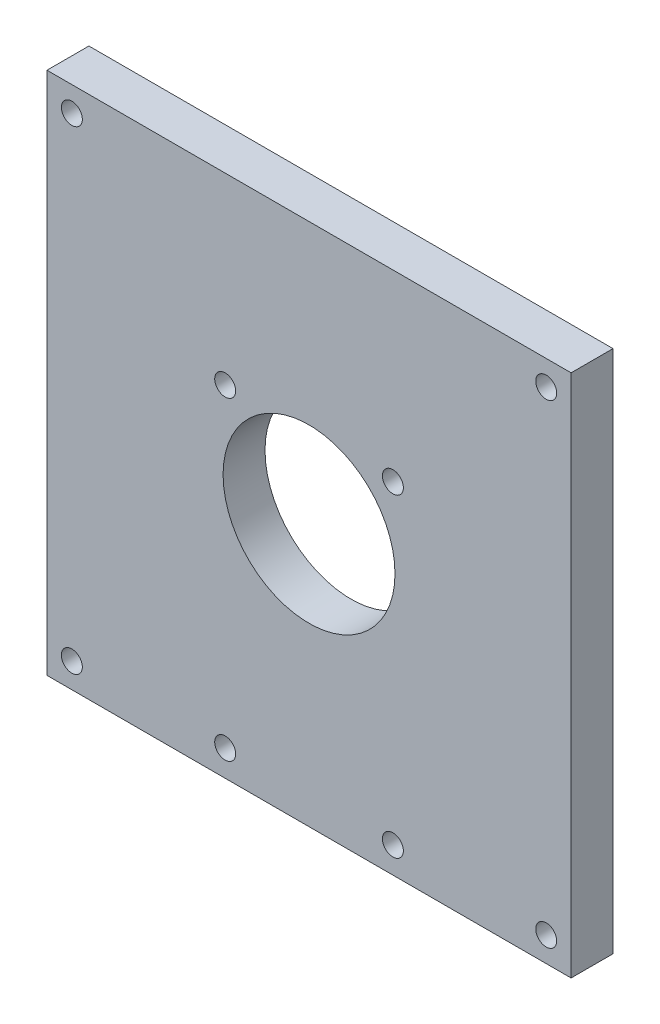
SolidWorks part; units mm, degrees
ref_plane "Front Plane" through (0, 0, 0) normal (0, 0, 1) x (1, 0, 0)
ref_plane "Top Plane" through (0, 0, 0) normal (0, 1, 0) x (1, 0, 0)
ref_plane "Right Plane" through (0, 0, 0) normal (1, 0, 0) x (0, 0, -1)
sketch "Sketch1" plane through (0, 0, 0) normal (0, 0, 1) x (1, 0, 0)
  line L1 (-25, -25) -> (25, -25)
  line L2 (-25, -25) -> (-25, 25)
  line L3 (-25, 25) -> (25, 25)
  line L4 (25, -25) -> (25, 25)
  line L5 (-25, -25) -> (25, 25) construction
  line L6 (-25, 25) -> (25, -25) construction
  circle A0 centre (-22.6274, 22.6274) radius 1
  circle A1 centre (22.6274, 22.6274) radius 1
  circle A2 centre (22.6274, -22.6274) radius 1
  circle A3 centre (-22.6274, -22.6274) radius 1
  point P0 (0, 0)
  dimension "D3" = 2
  dimension "D4" = 32
  dimension "D5" = 2
  dimension "D6" = 2
  dimension "D7" = 2
  dimension "D8" = 32
  dimension "D9" = 32
  dimension "D10" = 32
  dimension "D1" = 50
  dimension "D2" = 50
extrude "Boss-Extrude1" add sketch "Sketch1" along normal blind 4
sketch "Sketch2" plane through (0, 0, 4) normal (0, 0, 1) x (1, 0, 0)
  line L2 (-8, 7.5) -> (8, 7.5) construction
  line L3 (-8, 7.5) -> (-8, -22.5) construction
  line L4 (-8, -22.5) -> (8, -22.5) construction
  line L5 (8, 7.5) -> (8, -22.5) construction
  circle A0 centre (0, 0) radius 8.2
  circle A1 centre (-8, 7.5) radius 1
  circle A2 centre (8, 7.5) radius 1
  circle A3 centre (-8, -22.5) radius 1
  circle A4 centre (8, -22.5) radius 1
  point P7 (0, 7.5)
  dimension "D1" = 16.4
  dimension "D5" = 2
  dimension "D6" = 2
  dimension "D7" = 2
  dimension "D8" = 2
  dimension "D2" = 16
  dimension "D3" = 30
  dimension "D4" = 7.5
extrude "Cut-Extrude1" cut sketch "Sketch2" against normal blind 10
